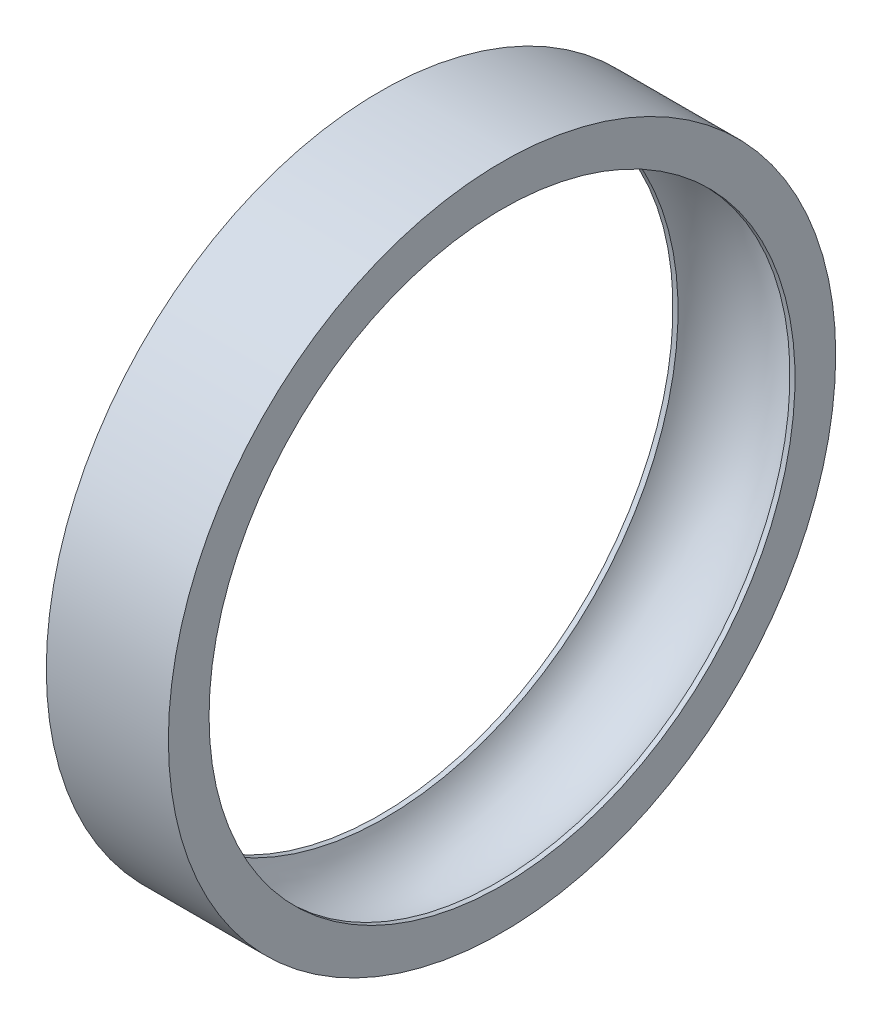
SolidWorks part; units mm, degrees
ref_plane "Front Plane" through (0, 0, 0) normal (0, 0, 1) x (1, 0, 0)
ref_plane "Top Plane" through (0, 0, 0) normal (0, 1, 0) x (1, 0, 0)
ref_plane "Right Plane" through (0, 0, 0) normal (1, 0, 0) x (0, 0, -1)
sketch "Sketch3" plane through (0, 0, 0) normal (0, 0, 1) x (1, 0, 0)
  line L0 (-7.5, 36) -> (-7.5, 41)
  line L1 (-7.5, 41) -> (7.5, 41)
  line L2 (7.5, 41) -> (7.5, 36)
  line L3 (-7.5, 36) -> (-6.8739, 36)
  line L4 (6.8739, 36) -> (7.5, 36)
  arc A1 (6.8739, 36) -> (-6.8739, 36) centre (0, 33) ccw
  point P0 (0, 41)
  dimension "D1" = 36
  dimension "D4" = 15
  dimension "D2" = 15
  dimension "D3" = 41
  dimension "D5" = 3
ref_axis "Axis1" through (0, 0, 0) along (1, 0, 0)
revolve "Revolve1" add sketch "Sketch3" angle 360 about axis through (0, 0, 0) along (1, 0, 0)
scale "Scale1" scale about centroid uniform scaling yes scale factor 1.9329
scale "Scale2" scale about centroid uniform scaling yes scale factor 1.5
